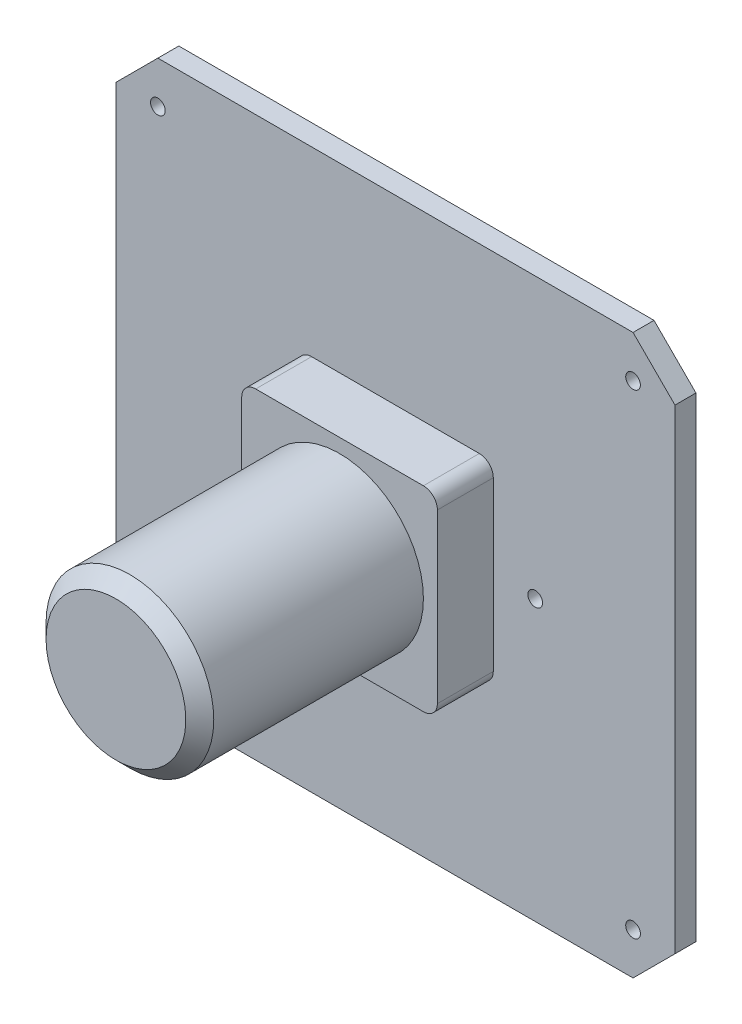
SolidWorks part; units mm, degrees
ref_plane "Front Plane" through (0, 0, 0) normal (0, 0, 1) x (1, 0, 0)
ref_plane "Top Plane" through (0, 0, 0) normal (0, 1, 0) x (1, 0, 0)
ref_plane "Right Plane" through (0, 0, 0) normal (1, 0, 0) x (0, 0, -1)
sketch "Sketch1" plane through (0, 0, 0) normal (0, 0, 1) x (1, 0, 0)
  line L0 (-20, 17) -> (-17, 20)
  line L1 (-17, -20) -> (17, -20)
  line L2 (-20, -17) -> (-20, 17)
  line L3 (-17, 20) -> (17, 20)
  line L4 (20, -17) -> (20, 17)
  line L5 (-18.5, -18.5) -> (18.5, 18.5) construction
  line L6 (-18.5, 18.5) -> (18.5, -18.5) construction
  line L7 (17, 20) -> (20, 17)
  line L8 (20, -17) -> (17, -20)
  line L9 (-17, -20) -> (-20, -17)
  line L10 (-20, 20) -> (-17, 20) construction
  line L11 (-20, 20) -> (-18.5, 18.5) construction
  line L12 (-20, 17) -> (-20, 20) construction
  line L13 (17, 20) -> (20, 20) construction
  line L14 (18.5, 18.5) -> (20, 20) construction
  line L15 (20, 17) -> (20, 20) construction
  line L16 (20, -20) -> (20, -17) construction
  line L17 (18.5, -18.5) -> (20, -20) construction
  line L18 (17, -20) -> (20, -20) construction
  line L19 (-20, -20) -> (-20, -17) construction
  line L20 (-20, -20) -> (-18.5, -18.5) construction
  line L21 (-20, -20) -> (-17, -20) construction
  line L22 (-10, 0) -> (10, 0) construction
  circle A0 centre (-17, 17) radius 0.525
  circle A1 centre (17, 17) radius 0.525
  circle A2 centre (17, -17) radius 0.525
  circle A3 centre (-17, -17) radius 0.525
  circle A4 centre (10, 0) radius 0.525
  circle A5 centre (-10, 0) radius 0.525
  point P0 (0, 0)
  point P24 (2.2523, 8.289)
  point P25 (8.2786, 0)
  point P26 (-17, 0)
  point P33 (0, 0)
  point P34 (0, 20)
  dimension "D4" = 1.05
  dimension "D1" = 40
  dimension "D2" = 40
  dimension "D3" = 34
  dimension "D5" = 20
  dimension "D6" = 20
extrude "Boss-Extrude1" add sketch "Sketch1" along normal blind 1.5
sketch "Sketch3" plane through (0, 0, 1.5) normal (0, 0, 1) x (1, 0, 0)
  line L0 (-7, -7) -> (-7, -6) construction
  line L1 (-6, -7) -> (6, -7)
  line L2 (-7, -6) -> (-7, 6)
  line L3 (-6, 7) -> (6, 7)
  line L4 (7, -6) -> (7, 6)
  line L5 (-6.7071, -6.7071) -> (6.7071, 6.7071) construction
  line L6 (-6.7071, 6.7071) -> (6.7071, -6.7071) construction
  line L7 (-7, -7) -> (-6.7071, -6.7071) construction
  line L8 (-7, -7) -> (-6, -7) construction
  line L9 (7, -7) -> (7, -6) construction
  line L10 (6.7071, -6.7071) -> (7, -7) construction
  line L11 (6, -7) -> (7, -7) construction
  line L12 (6, 7) -> (7, 7) construction
  line L13 (6.7071, 6.7071) -> (7, 7) construction
  line L14 (7, 6) -> (7, 7) construction
  line L15 (-7, 7) -> (-6, 7) construction
  line L16 (-7, 7) -> (-6.7071, 6.7071) construction
  line L17 (-7, 6) -> (-7, 7) construction
  arc A0 (-6, 7) -> (-7, 6) centre (-6, 6) ccw
  arc A1 (7, 6) -> (6, 7) centre (6, 6) ccw
  arc A2 (6, -7) -> (7, -6) centre (6, -6) ccw
  arc A3 (-7, -6) -> (-6, -7) centre (-6, -6) ccw
  arc A4 (-5.2929, 5.2929) -> (-6, 7) centre (-6, 6) ccw construction
  arc A5 (-7, 6) -> (-5.2929, 5.2929) centre (-6, 6) ccw construction
  arc A6 (-5.2929, -5.2929) -> (-7, -6) centre (-6, -6) ccw construction
  arc A7 (-6, -7) -> (-5.2929, -5.2929) centre (-6, -6) ccw construction
  arc A8 (5.2929, -5.2929) -> (6, -7) centre (6, -6) ccw construction
  arc A9 (7, -6) -> (5.2929, -5.2929) centre (6, -6) ccw construction
  arc A10 (5.2929, 5.2929) -> (7, 6) centre (6, 6) ccw construction
  arc A11 (6, 7) -> (5.2929, 5.2929) centre (6, 6) ccw construction
  point P0 (0, 0)
  dimension "D2" = 1
  dimension "D1" = 14
extrude "Boss-Extrude2" add sketch "Sketch3" along normal blind 4
sketch "Sketch4" plane through (0, 0, 0) normal (0, 1, 0) x (1, 0, 0)
  line L0 (0, -1000) -> (0, 49000) construction
  line L2 (0, -5.5) -> (-6, -5.5)
  line L3 (6, -5.5) -> (-6, -5.5) construction
  line L4 (-6, -5.5) -> (-6, -21.5)
  line L5 (-6, -21.5) -> (0, -21.5)
  line L6 (0, -21.5) -> (0, -5.5)
  dimension "D1" = 12
  dimension "D2" = 16
revolve "Revolve1" add sketch "Sketch4" angle 360 about L0
chamfer "Chamfer1" distance 1 angle 45 1 edges at (6, 0, 21.5)
